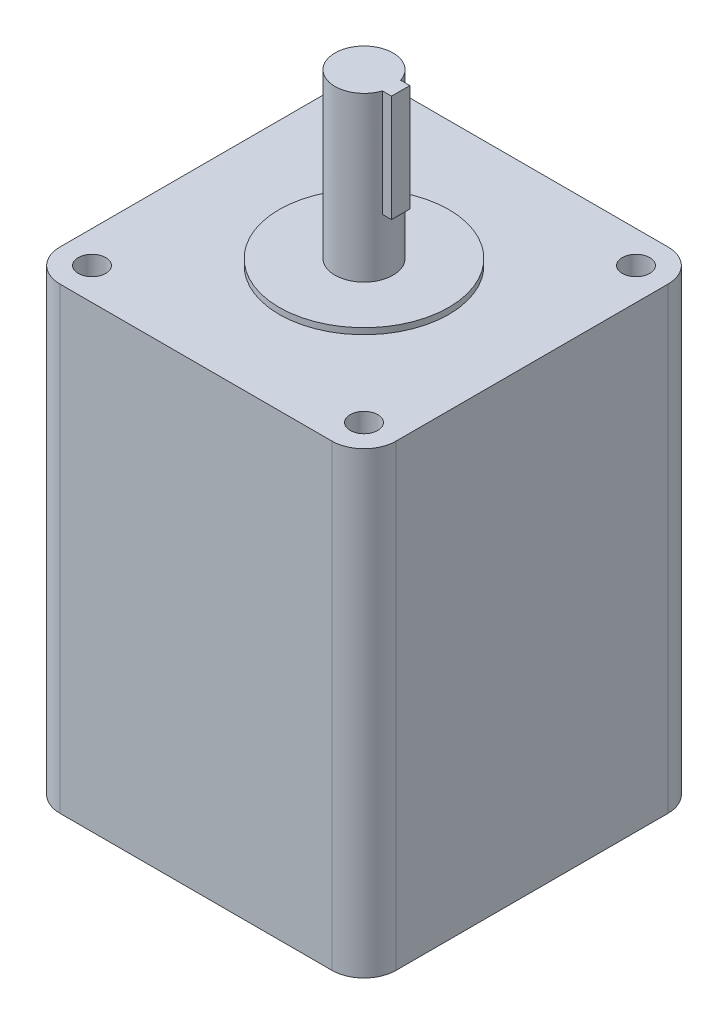
SolidWorks part; units mm, degrees
ref_plane "Front Plane" through (0, 0, 0) normal (0, 0, 1) x (1, 0, 0)
ref_plane "Top Plane" through (0, 0, 0) normal (0, 1, 0) x (1, 0, 0)
ref_plane "Right Plane" through (0, 0, 0) normal (1, 0, 0) x (0, 0, -1)
sketch "Sketch1" plane through (0, 0, 0) normal (0, 1, 0) x (1, 0, 0)
  line L1 (-44.5, 55) -> (44.5, 55)
  line L2 (-55, 44.5) -> (-55, -44.5)
  line L3 (-44.5, -55) -> (44.5, -55)
  line L4 (55, 44.5) -> (55, -44.5)
  arc A0 (-44.5, 55) -> (-55, 44.5) centre (-44.5, 44.5) ccw
  arc A1 (55, 44.5) -> (44.5, 55) centre (44.5, 44.5) ccw
  arc A2 (-44.5, -55) -> (-55, -44.5) centre (-44.5, -44.5) cw
  arc A3 (55, -44.5) -> (44.5, -55) centre (44.5, -44.5) cw
  point P0 (0, 0)
  dimension "D1" = 89
  dimension "D7" = 62.9325
  dimension "D8" = 10.5
  dimension "D9" = 10.5
  dimension "D10" = 10.5
  dimension "D11" = 10.5
  dimension "D2" = 110
  dimension "D3" = 89
  dimension "D4" = 110
  dimension "D5" = 55
  dimension "D6" = 55
  dimension "D12" = 62.9325
  dimension "D13" = 89
  dimension "D14" = 89
extrude "Boss-Extrude1" add sketch "Sketch1" along normal blind 150 contours L2 A2 L3 A3 L4 A1 L1 A0
sketch "Sketch2" plane through (0, 150, 0) normal (0, 1, 0) x (1, 0, 0)
  line L0 (-55, 44.5) -> (-55, -44.5) construction
  line L1 (-44.5, -55) -> (44.5, -55) construction
  line L2 (-44.5, 55) -> (44.5, 55) construction
  line L3 (55, 44.5) -> (55, -44.5) construction
  circle A2 centre (-44.5, 44.5) radius 4.5
  circle A3 centre (44.5, 44.5) radius 4.5
  circle A4 centre (-44.5, -44.5) radius 4.5
  circle A5 centre (44.5, -44.5) radius 4.5
  dimension "D1" = 9
  dimension "D2" = 9
  dimension "D3" = 9
  dimension "D4" = 9
  dimension "D5" = 62.9325
  dimension "D6" = 10.5
  dimension "D7" = 62.9325
  dimension "D8" = 10.5
  dimension "D9" = 62.9325
  dimension "D10" = 62.9325
  dimension "D11" = 10.5
  dimension "D12" = 10.5
extrude "Cut-Extrude2" cut sketch "Sketch2" against normal blind 12.5 contours A5 | A4 | A3 | A2
sketch "Sketch3" plane through (0, 150, 0) normal (0, 1, 0) x (1, 0, 0)
  circle A0 centre (0, 0) radius 9.5
  dimension "D1" = 19
extrude "Boss-Extrude2" add sketch "Sketch3" along normal blind 55.5
sketch "Sketch4" plane through (0, 150, 0) normal (0, 1, 0) x (1, 0, 0)
  circle A0 centre (0, 0) radius 27.75
  dimension "D1" = 55.5
extrude "Boss-Extrude3" add sketch "Sketch4" along normal blind 2
sketch "Sketch5" plane through (0, 0, 0) normal (1, 0, 0) x (0, 0, -1)
  line L6 (9.5, 205.5) -> (-9.5, 205.5) construction
  line L7 (3, 170.5) -> (-3, 170.5)
  line L8 (-3, 170.5) -> (-3, 205.5)
  line L9 (-3, 205.5) -> (3, 205.5)
  line L10 (3, 170.5) -> (3, 205.5)
  point P10 (0, 170.5)
  dimension "D1" = 35
  dimension "D2" = 3
extrude "Boss-Extrude4" add sketch "Sketch5" along normal blind 12
